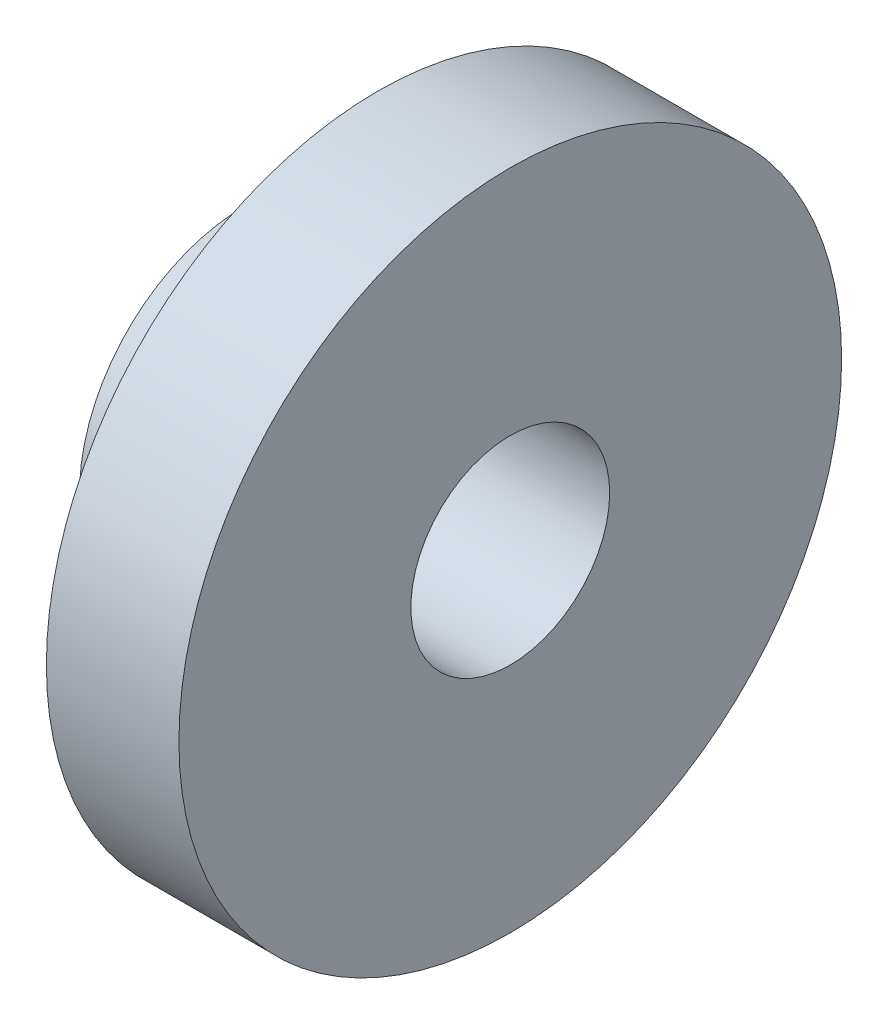
SolidWorks part; units mm, degrees
ref_plane "Front Plane" through (0, 0, 0) normal (0, 0, 1) x (1, 0, 0)
ref_plane "Top Plane" through (0, 0, 0) normal (0, 1, 0) x (1, 0, 0)
ref_plane "Right Plane" through (0, 0, 0) normal (1, 0, 0) x (0, 0, -1)
sketch "Sketch1" plane through (0, 0, 0) normal (1, 0, 0) x (0, 0, -1)
  circle A0 centre (0, 0) radius 1.5
  circle A1 centre (0, 0) radius 2.5
  dimension "D1" = 3
  dimension "D2" = 5
extrude "Boss-Extrude1" add sketch "Sketch1" along normal blind 2
sketch "Sketch2" plane through (2, 0, 0) normal (1, 0, 0) x (0, 0, -1)
  circle A0 centre (0, 0) radius 1.5
  circle A1 centre (0, 0) radius 5
  dimension "D1" = 10
extrude "Boss-Extrude2" add sketch "Sketch2" along normal blind 2
